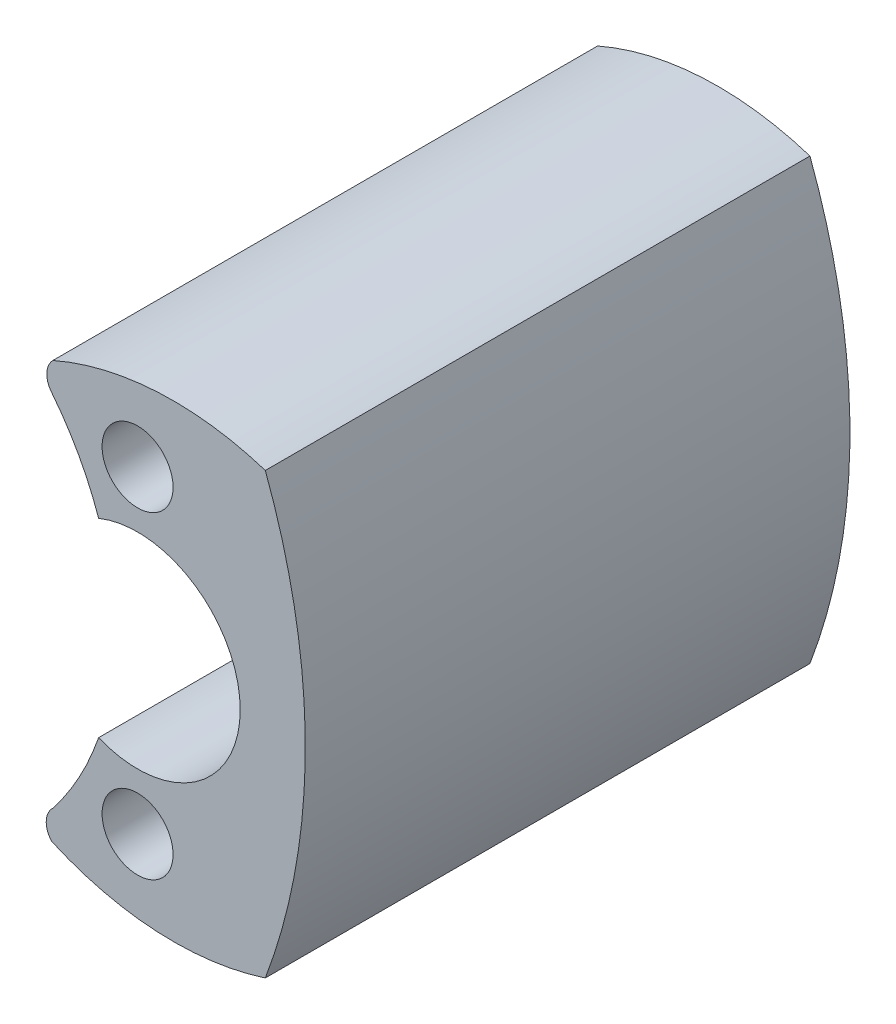
SolidWorks part; units mm, degrees
ref_plane "Front Plane" through (0, 0, 0) normal (0, 0, 1) x (1, 0, 0)
ref_plane "Top Plane" through (0, 0, 0) normal (0, 1, 0) x (1, 0, 0)
ref_plane "Right Plane" through (0, 0, 0) normal (1, 0, 0) x (0, 0, -1)
sketch "Sketch1" plane through (0, 0, 0) normal (0, 0, 1) x (1, 0, 0)
  line L0 (0, 0) -> (0, 9.5) construction
  arc A0 (5.3943, 9.2817) -> (5.3943, -9.2817) centre (-19.2657, 0) cw
  arc A1 (-3.6387, 7.6355) -> (-3.5758, 8.8197) centre (-2.9394, 8.1921) cw
  arc A2 (-3.5758, 8.8197) -> (5.3943, 9.2817) centre (1.5165, -2.7402) cw
  arc A3 (-3.6387, 7.6355) -> (-3.5758, -7.5558) centre (-13.2313, 0) cw
  arc A5 (-3.5758, -7.5558) -> (-3.6256, -8.7977) centre (-2.9797, -8.2016) ccw
  arc A7 (-3.6256, -8.7977) -> (5.3943, -9.2817) centre (1.5165, 2.7402) ccw
extrude "Extrude1" add sketch "Sketch1" along normal blind 23 and the other way blind 0.001
sketch "Sketch3" plane through (0, 0, 23) normal (0, 0, 1) x (1, 0, 0)
  circle A0 centre (0, 6.715) radius 1.5
  circle A1 centre (0, -6.715) radius 1.5
  dimension "D1" = 3
  dimension "D2" = 13.43
extrude "Cut-Extrude1" cut sketch "Sketch3" against normal through all
sketch "Sketch5" plane through (0, 0, -0.001) normal (0, 0, -1) x (-1, 0, 0)
  circle A0 centre (0, 0) radius 4.335
  dimension "D1" = 8.67
extrude "Cut-Extrude2" cut sketch "Sketch5" against normal blind 24
